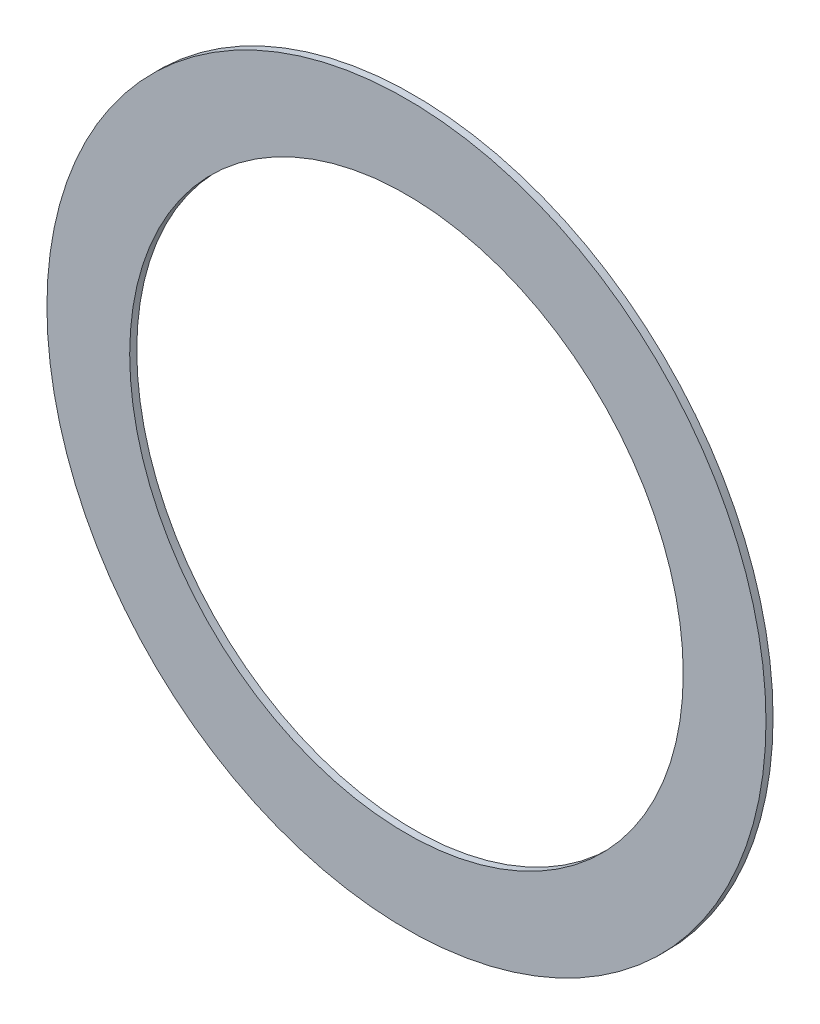
SolidWorks part; units mm, degrees
ref_plane "Front Plane" through (0, 0, 0) normal (0, 0, 1) x (1, 0, 0)
ref_plane "Top Plane" through (0, 0, 0) normal (0, 1, 0) x (1, 0, 0)
ref_plane "Right Plane" through (0, 0, 0) normal (1, 0, 0) x (0, 0, -1)
sketch "Sketch1" plane through (0, 0, 0) normal (0, 0, 1) x (1, 0, 0)
  line L0 (-31.75, 0) -> (31.75, 0) construction
  circle A0 centre (0, 0) radius 41.275 construction
  circle A1 centre (0, 0) radius 31.7754 construction
  dimension "OD" = 82.55
  dimension "ID" = 63.5508
  dimension "For Shaft Diameter" = 63.5
sketch "Sketch2" plane through (0, 0, 0) normal (1, 0, 0) x (0, 0, -1)
  line L4 (0.4064, 41.275) -> (-0.4064, 41.275) construction
  point P0 (0, 41.275)
  dimension "Thickness" = 0.8128
sketch "Sketch3" plane through (0, 0, 0) normal (0, 0, 1) x (1, 0, 0)
  circle A0 centre (0, 0) radius 31.7754 construction
  circle A1 centre (0, 0) radius 41.275 construction
  circle A3 centre (0, 0) radius 31.7754
  circle A5 centre (0, 0) radius 41.275
extrude "Boss-Extrude1" add sketch "Sketch3" against normal up to vertex (0.4064 mm away) and the other way up to vertex (0.4064 mm away)
equation "\"D1\"= \"Thickness@Sketch2\""
